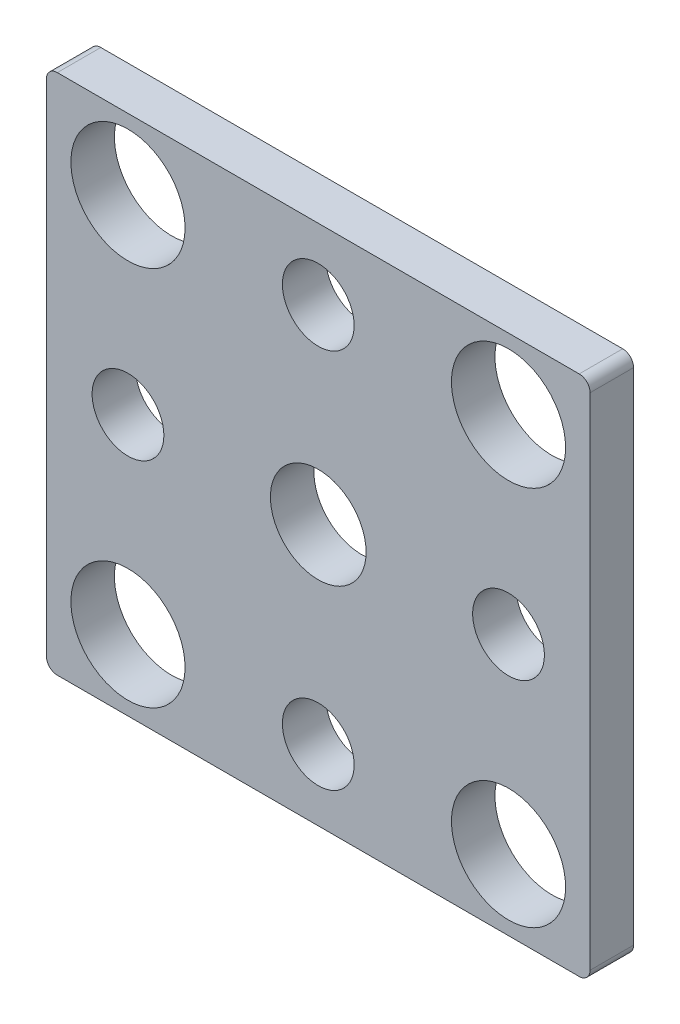
SolidWorks part; units mm, degrees
ref_plane "前视基准面" through (0, 0, 0) normal (0, 0, 1) x (1, 0, 0)
ref_plane "上视基准面" through (0, 0, 0) normal (0, 1, 0) x (1, 0, 0)
ref_plane "右视基准面" through (0, 0, 0) normal (1, 0, 0) x (0, 0, -1)
other "Configuration Table"
sketch "草图1" plane through (0, 0, 0) normal (0, 0, 1) x (1, 0, 0)
  line L0 (0, 0) -> (50, 0)
  line L1 (50, 0) -> (50, -48)
  line L2 (50, -48) -> (0, -48)
  line L3 (0, -48) -> (0, 0)
  dimension "D1" = 50
  dimension "D2" = 48
extrude "凸台-拉伸1" add sketch "草图1" along normal blind 4
sketch "草图2" plane through (0, 0, 4) normal (0, 0, 1) x (1, 0, 0)
  line L0 (50, -24) -> (0, -24)
  line L1 (50, -48) -> (50, 0) construction
  line L2 (0, 0) -> (0, -48) construction
  line L3 (25, 0) -> (25, -48)
  line L4 (50, 0) -> (0, 0) construction
  line L5 (0, -48) -> (50, -48) construction
  line L6 (25, -24) -> (25, -12)
  circle A0 centre (42.5, -6.5) radius 5.25
  circle A1 centre (42.5, -41.5) radius 5.25
  circle A2 centre (7.5, -41.5) radius 5.25
  circle A3 centre (7.5, -6.5) radius 5.25
  circle A4 centre (25, -24) radius 4.4
  dimension "D1" = 17.5
  dimension "D3" = 10.5
  dimension "D4" = 8.8
  dimension "D2" = 17.5
fillet "圆角1" radius 1 4 edges at (50, -48, 2) (0, -48, 2) (0, 0, 2) (50, 0, 2)
sketch "草图8" plane through (0, 0, 4) normal (0, 0, 1) x (1, 0, 0)
  line L5 (25, -48) -> (25, 0)
  line L6 (1, -48) -> (49, -48) construction
  line L7 (49, 0) -> (1, 0) construction
  line L8 (50, -24) -> (0, -24)
  line L9 (50, -47) -> (50, -1) construction
  line L10 (0, -1) -> (0, -47) construction
  line L11 (25, -24) -> (55, -24)
  line L12 (25, -24) -> (-5, -24)
  circle A0 centre (-5, -24) radius 3.3648
  circle A1 centre (25, -24) radius 3.7667
  circle A2 centre (55, -24) radius 3.2192
  circle A3 centre (40, -24) radius 3.2586
  circle A4 centre (10, -24) radius 3.1199
  dimension "D3" = 15
  dimension "D1" = 30
  dimension "D2" = 60
  dimension "D4" = 15
extrude "切除-拉伸1" cut sketch "草图2" against normal through all contours A3 | A0 | A1 | A2 | L0 A4 L6 | L6 A4 L0 | L0 A4 L3 | L3 A4 L0
sketch "草图9" plane through (0, 0, 4) normal (0, 0, 1) x (1, 0, 0)
  line L0 (50, -24) -> (0, -24)
  line L1 (50, -47) -> (50, -1) construction
  line L2 (0, -1) -> (0, -47) construction
  line L3 (25, -48) -> (25, 0)
  line L4 (1, -48) -> (49, -48) construction
  line L5 (49, 0) -> (1, 0) construction
  circle A0 centre (25, -6.5) radius 3.3
  circle A1 centre (42.5, -24) radius 3.3
  circle A2 centre (25, -41.5) radius 3.3
  circle A3 centre (7.5, -24) radius 3.3
  point P15 (25, -24)
  point P23 (25, -24)
  dimension "D1" = 4
  dimension "D2" = 17.5
extrude "切除-拉伸2" cut sketch "草图9" against normal through all contours L0 A3 | L0 A3 | L0 A1 | L0 A1 | L3 A0 | L3 A0 | L3 A2 | L3 A2
